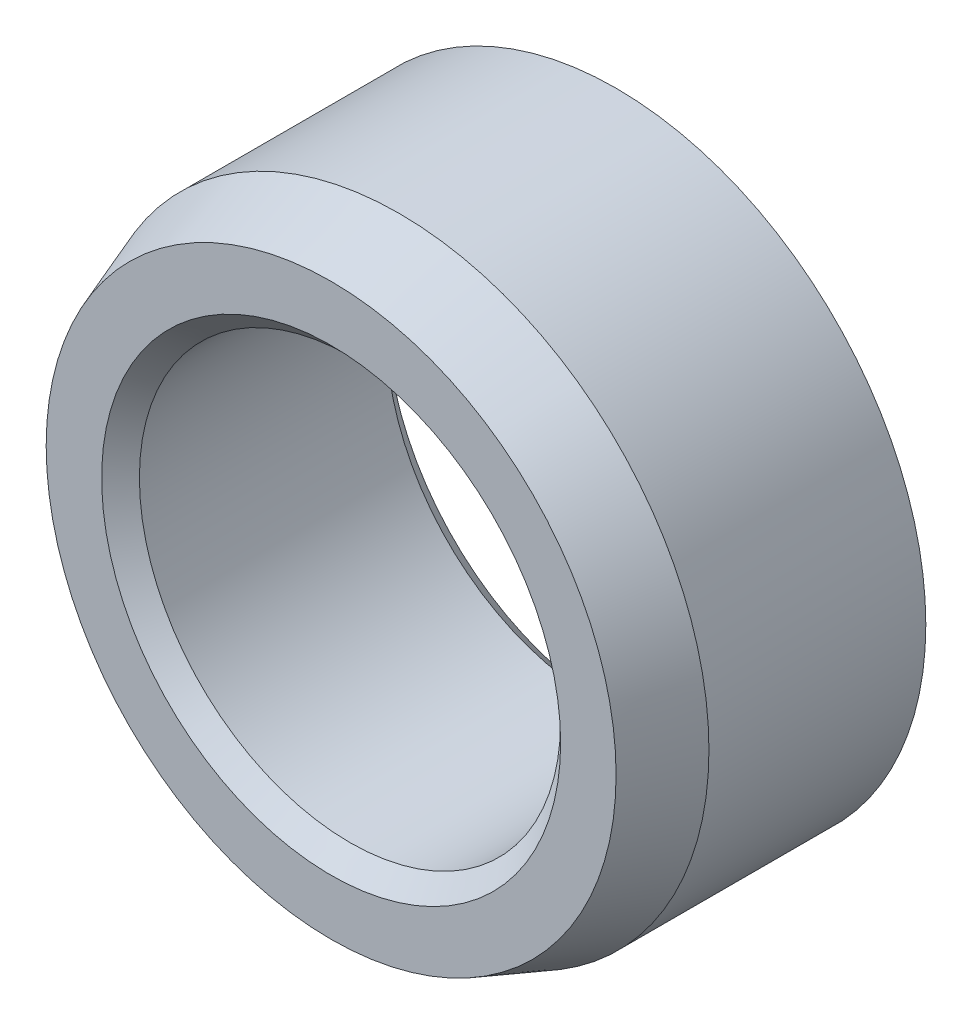
SolidWorks part; units mm, degrees
material "8620 STEEL"
ref_plane "Front Plane" through (0, 0, 0) normal (0, 0, 1) x (1, 0, 0)
ref_plane "Top Plane" through (0, 0, 0) normal (0, 1, 0) x (1, 0, 0)
ref_plane "Right Plane" through (0, 0, 0) normal (1, 0, 0) x (0, 0, -1)
sketch "Sketch1" plane through (0, 0, 0) normal (1, 0, 0) x (0, 0, -1)
  line L0 (-30.27, 0) -> (59.9369, 0) construction
  line L1 (0.762, 8.5) -> (10.738, 8.5)
  line L2 (11.5, 9.262) -> (11.5, 12.5)
  line L3 (0, 9.262) -> (0.762, 8.5)
  line L4 (11.5, 12.5) -> (2.7475, 12.5)
  line L5 (2.7475, 12.5) -> (0, 11.5)
  line L6 (0, 11.5) -> (0, 9.262)
  line L7 (10.738, 8.5) -> (11.5, 9.262)
  point P3 (0, 8.5)
  point P4 (11.5, 8.5)
  dimension "D1" = 25
  dimension "D2" = 17
  dimension "D3" = 20
  dimension "D4" = 0.762
  dimension "D5" = 3
  dimension "D6" = 11.5
  dimension "D7" = 45
  dimension "D8" = 0.762
  dimension "D9" = 45
revolve "Revolve1" add sketch "Sketch1" angle 360 about L0
